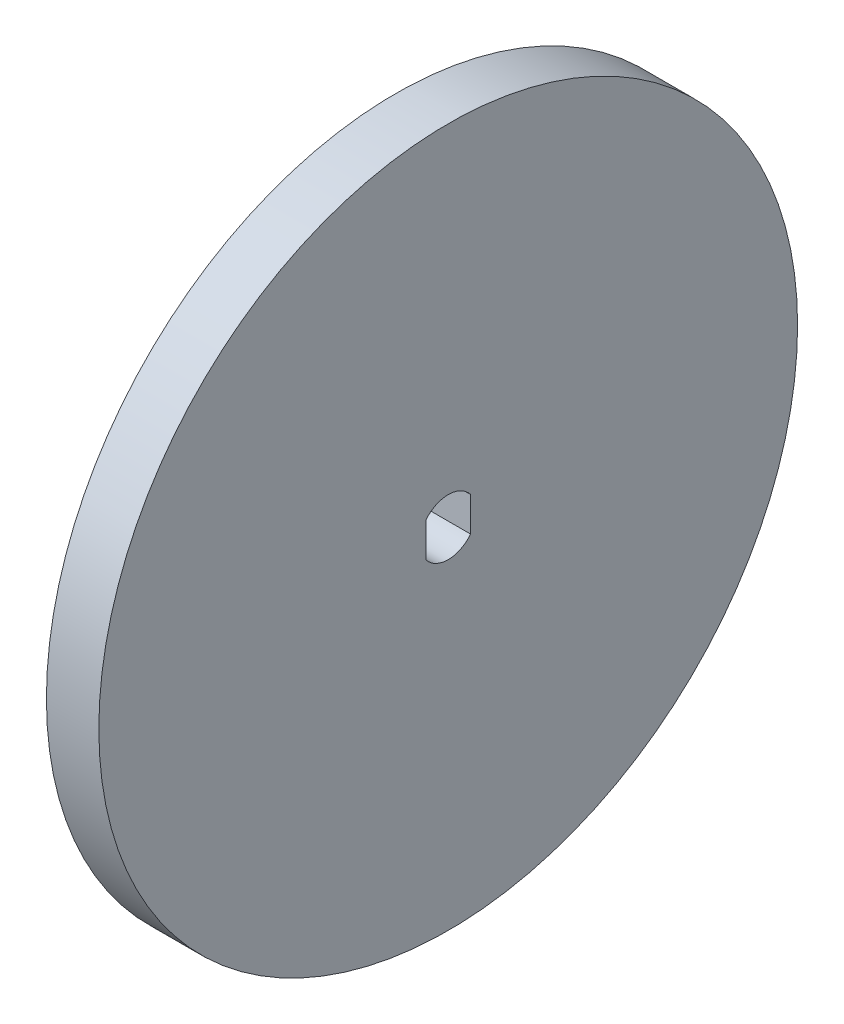
SolidWorks part; units mm, degrees
ref_plane "Front Plane" through (0, 0, 0) normal (0, 0, 1) x (1, 0, 0)
ref_plane "Top Plane" through (0, 0, 0) normal (0, 1, 0) x (1, 0, 0)
ref_plane "Right Plane" through (0, 0, 0) normal (1, 0, 0) x (0, 0, -1)
sketch "Sketch1" plane through (0, 0, 0) normal (1, 0, 0) x (0, 0, -1)
  line L0 (1.15, 0.8832) -> (1.15, -0.8832)
  line L1 (-1.15, 0.8832) -> (-1.15, -0.8832)
  line L2 (-1.15, 0) -> (1.15, 0) construction
  circle A0 centre (0, 0) radius 18
  arc A1 (1.15, 0.8832) -> (-1.15, 0.8832) centre (0, 0) ccw
  arc A2 (-1.15, -0.8832) -> (1.15, -0.8832) centre (0, 0) ccw
  dimension "D1" = 36
  dimension "D2" = 2.9
  dimension "D3" = 2.3
extrude "Base" add sketch "Sketch1" along normal blind 2.7
